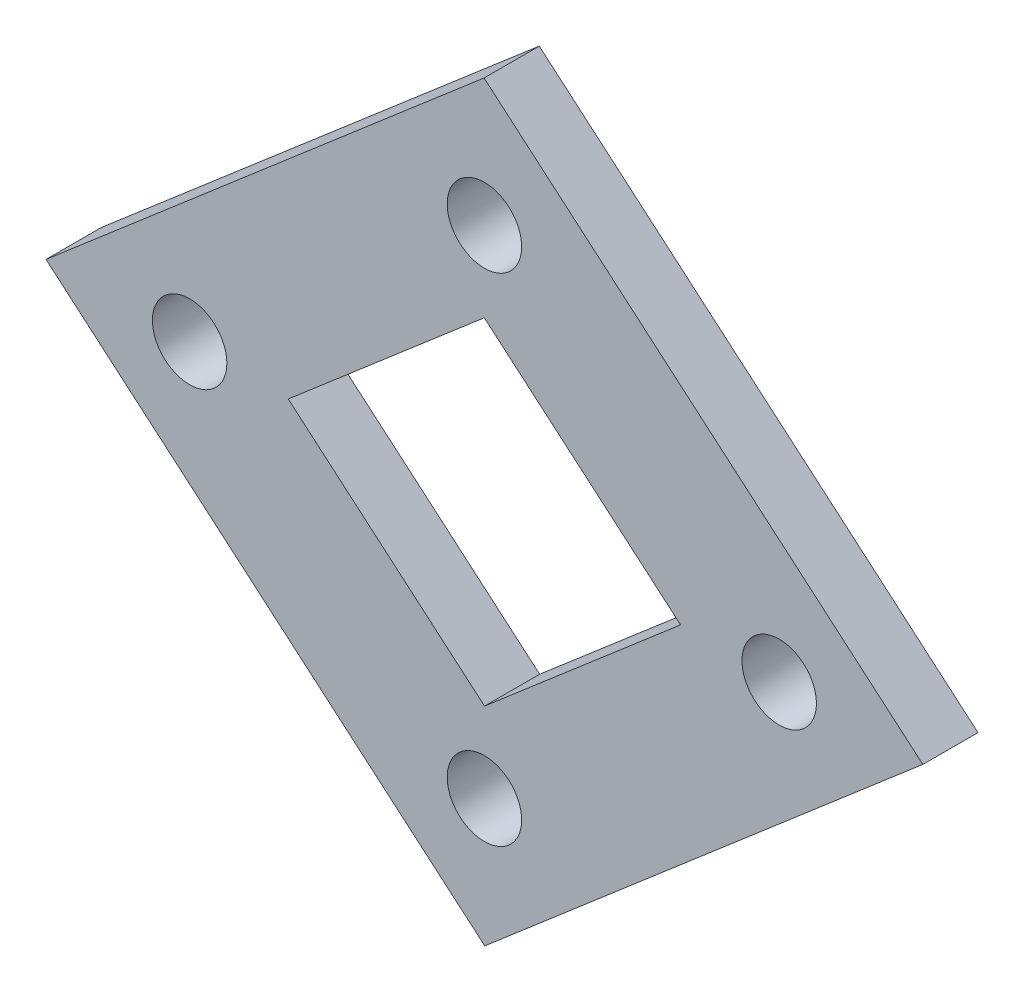
SolidWorks part; units mm, degrees
material "Delrin 2700 NC010, Low Viscosity Acetal Copolymer (SS)"
ref_plane "Front Plane" through (0, 0, 0) normal (0, 0, 1) x (1, 0, 0)
ref_plane "Top Plane" through (0, 0, 0) normal (0, 1, 0) x (1, 0, 0)
ref_plane "Right Plane" through (0, 0, 0) normal (1, 0, 0) x (0, 0, -1)
sketch "Sketch1" plane through (0, 0, 0) normal (0, 0, 1) x (1, 0, 0)
  line L0 (-9.5, 0) -> (9.5, 0) construction
  line L1 (0, 8) -> (0, -8) construction
  line L2 (0, 0) -> (0, 8) construction
  line L3 (0, 0) -> (0, -8) construction
  line L4 (0, 0) -> (-9.5, 0) construction
  line L5 (-9.5, 0) -> (0, 8) construction
  line L6 (-14.1292, -0.0169) -> (0.0109, -12.1065)
  line L8 (-14.1292, -0.0169) -> (-0.0109, 12.1065)
  line L9 (0.0109, -12.1065) -> (14.1292, 0.0169)
  line L10 (-0.0109, 12.1065) -> (14.1292, 0.0169)
  line L11 (-14.1292, -0.0169) -> (14.1292, 0.0169) construction
  circle A0 centre (0, 8) radius 1.2
  circle A1 centre (-9.5, 0) radius 1.2
  circle A2 centre (9.5, 0) radius 1.2
  circle A3 centre (0, -8) radius 1.2
  circle A17 centre (-17.2517, -6.6911) radius 1.016 [skipped]
  circle A18 centre (-6.6798, 17.2438) radius 1.016 [skipped]
  circle A19 centre (17.2551, 6.6718) radius 1.016 [skipped]
  circle A20 centre (6.6831, -17.263) radius 1.016 [skipped]
  point P3 (0, 0)
  point P8 (0, 0)
  point P13 (0, 0)
  point P20 (0.0113, -0.008)
  point P23 (0.0033, -0.0193)
  point P26 (-0.008, -0.0113)
  dimension "D3" = 2.4
  dimension "D8" = 2
  dimension "D10" = 2.4
  dimension "D11" = 2
  dimension "D1" = 19
  dimension "D2" = 16
  dimension "D9" = 8
  dimension "D12" = 9.5
  dimension "D7" = 4
extrude "Boss-Extrude1" add sketch "Sketch1" along normal blind 1.778
sketch "Sketch2" plane through (0, 0, 1.778) normal (0, 0, 1) x (1, 0, 0)
  line L8 (-0.0037, 5.4167) -> (-6.3217, -0.0085)
  line L9 (-6.3217, -0.0085) -> (0.0037, -5.4167)
  line L10 (0.0037, -5.4167) -> (6.3217, 0.0085)
  line L11 (6.3217, 0.0085) -> (-0.0037, 5.4167)
  line L12 (-0.0037, 5.4167) -> (-6.3217, -0.0085)
  line L13 (-6.3217, -0.0085) -> (0.0037, -5.4167)
  line L14 (0.0037, -5.4167) -> (6.3217, 0.0085)
  line L15 (6.3217, 0.0085) -> (-0.0037, 5.4167)
  dimension "D1" = 5.08
extrude "Cut-Extrude1" cut sketch "Sketch2" against normal up to next
